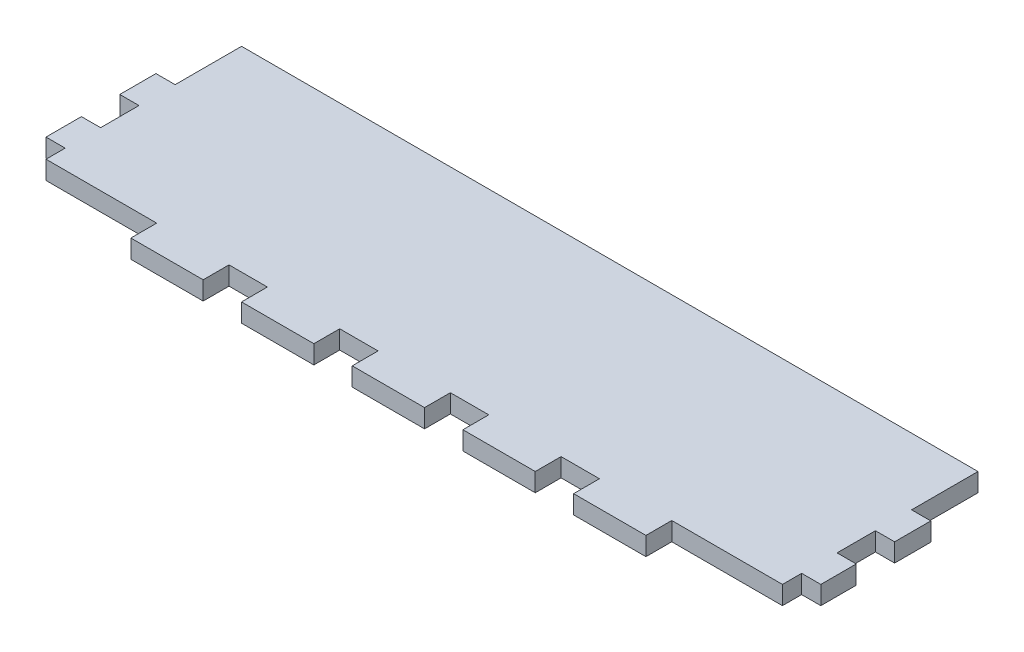
SolidWorks part; units mm, degrees
ref_plane "Front Plane" through (0, 0, 0) normal (0, 0, 1) x (1, 0, 0)
ref_plane "Top Plane" through (0, 0, 0) normal (0, 1, 0) x (1, 0, 0)
ref_plane "Right Plane" through (0, 0, 0) normal (1, 0, 0) x (0, 0, -1)
sketch "Sketch1" plane through (0, 0, 0) normal (0, 1, 0) x (1, 0, 0)
  line L2 (-133.35, -28.575) -> (-133.35, 28.575)
  line L3 (-133.35, 28.575) -> (133.35, 28.575)
  line L4 (133.35, -28.575) -> (133.35, 28.575)
  line L5 (-133.35, -28.575) -> (133.35, 28.575) construction
  line L6 (-133.35, 28.575) -> (133.35, -28.575) construction
  line L11 (-133.35, -28.575) -> (133.35, -28.575)
  point P0 (0, 0)
  dimension "D1" = 57.15
  dimension "D2" = 266.7
extrude "Boss-Extrude1" add sketch "Sketch1" along normal blind 6.35
sketch "Sketch3" plane through (0, 0, 0) normal (0, 1, 0) x (1, 0, 0)
  line L0 (-133.35, -28.575) -> (133.35, -28.575) construction
  line L1 (-88.646, -28.575) -> (-88.646, -37.465)
  line L2 (-88.646, -37.465) -> (-63.754, -37.465)
  line L3 (-63.754, -37.465) -> (-63.754, -28.575)
  line L4 (-63.754, -28.575) -> (-88.646, -28.575)
  line L5 (-50.546, -28.575) -> (-50.546, -37.465)
  line L6 (-50.546, -37.465) -> (-25.654, -37.465)
  line L7 (-25.654, -37.465) -> (-25.654, -28.575)
  line L8 (-25.654, -28.575) -> (-50.546, -28.575)
  line L9 (-12.446, -28.575) -> (-12.446, -37.465)
  line L10 (-12.446, -37.465) -> (12.446, -37.465)
  line L11 (12.446, -37.465) -> (12.446, -28.575)
  line L12 (12.446, -28.575) -> (-12.446, -28.575)
  line L13 (25.654, -28.575) -> (25.654, -37.465)
  line L14 (25.654, -37.465) -> (50.546, -37.465)
  line L15 (50.546, -37.465) -> (50.546, -28.575)
  line L16 (50.546, -28.575) -> (25.654, -28.575)
  line L17 (63.754, -28.575) -> (63.754, -37.465)
  line L18 (63.754, -37.465) -> (88.646, -37.465)
  line L19 (88.646, -37.465) -> (88.646, -28.575)
  line L20 (88.646, -28.575) -> (63.754, -28.575)
  point P0 (-76.2, -28.575)
  point P6 (-38.1, -28.575)
  point P14 (0, -28.575)
  point P19 (38.1, -28.575)
  point P24 (76.2, -28.575)
  dimension "D1" = 24.892
  dimension "D2" = 8.89
  dimension "D3" = 57.15
  dimension "D4" = 5
extrude "Boss-Extrude2" add sketch "Sketch3" along normal blind 6.35
sketch "Sketch4" plane through (0, 0, 0) normal (0, 1, 0) x (1, 0, 0)
  line L0 (133.35, 28.575) -> (-133.35, 28.575) construction
  line L6 (-139.954, 28.829) -> (-126.746, 28.829)
  line L7 (-139.954, 28.829) -> (-139.954, 15.621)
  line L8 (0, 0) -> (0, 63.6475) construction
  line L13 (133.35, -28.575) -> (133.35, 28.575) construction
  line L14 (126.746, 28.829) -> (139.954, 28.829)
  line L30 (126.746, 28.829) -> (126.746, 15.621)
  line L31 (126.746, 15.621) -> (139.954, 15.621)
  line L32 (139.954, 28.829) -> (139.954, 15.621)
  line L33 (126.746, 28.829) -> (139.954, 15.621) construction
  line L34 (126.746, 15.621) -> (139.954, 28.829) construction
  line L36 (-139.954, 15.621) -> (-126.746, 15.621)
  line L37 (-126.746, 28.829) -> (-126.746, 15.621)
  line L38 (-139.954, 28.829) -> (-126.746, 15.621) construction
  line L39 (-139.954, 15.621) -> (-126.746, 28.829) construction
  line L40 (-139.954, 3.429) -> (-126.746, 3.429)
  line L41 (-139.954, 3.429) -> (-139.954, -9.779)
  line L42 (-139.954, -9.779) -> (-126.746, -9.779)
  line L43 (-126.746, 3.429) -> (-126.746, -9.779)
  line L44 (-139.954, 3.429) -> (-126.746, -9.779) construction
  line L45 (-139.954, -9.779) -> (-126.746, 3.429) construction
  line L46 (-139.954, -21.971) -> (-126.746, -21.971)
  line L47 (-139.954, -21.971) -> (-139.954, -35.179)
  line L48 (-139.954, -35.179) -> (-126.746, -35.179)
  line L49 (-126.746, -21.971) -> (-126.746, -35.179)
  line L50 (-139.954, -21.971) -> (-126.746, -35.179) construction
  line L51 (-139.954, -35.179) -> (-126.746, -21.971) construction
  line L52 (126.746, 3.429) -> (139.954, 3.429)
  line L53 (126.746, 3.429) -> (126.746, -9.779)
  line L54 (126.746, -9.779) -> (139.954, -9.779)
  line L55 (139.954, 3.429) -> (139.954, -9.779)
  line L56 (126.746, 3.429) -> (139.954, -9.779) construction
  line L57 (126.746, -9.779) -> (139.954, 3.429) construction
  line L58 (126.746, -21.971) -> (139.954, -21.971)
  line L59 (126.746, -21.971) -> (126.746, -35.179)
  line L60 (126.746, -35.179) -> (139.954, -35.179)
  line L61 (139.954, -21.971) -> (139.954, -35.179)
  line L62 (126.746, -21.971) -> (139.954, -35.179) construction
  line L63 (126.746, -35.179) -> (139.954, -21.971) construction
  point P4 (-133.35, 22.225)
  point P10 (-133.35, -3.175)
  point P13 (133.35, 22.225)
  point P23 (-133.35, -28.575)
  point P29 (133.35, -3.175)
  point P34 (133.35, -28.575)
  dimension "D1" = 3
  dimension "D4" = 13.208
  dimension "D6" = 13.208
  dimension "D7" = 6.35
extrude "Cut-Extrude2" cut sketch "Sketch4" along normal through all
sketch "Sketch5" plane through (0, 6.35, 0) normal (0, 1, 0) x (1, 0, 0)
  line L0 (126.746, 28.575) -> (-126.746, 28.575) construction
  line L1 (-139.7688, 28.575) -> (155.6953, 28.575)
  line L2 (-139.7688, 28.575) -> (-139.7688, 15.875)
  line L3 (-139.7688, 15.875) -> (155.6953, 15.875)
  line L4 (155.6953, 28.575) -> (155.6953, 15.875)
  dimension "D1" = 12.7
extrude "Cut-Extrude3" cut sketch "Sketch5" against normal through all
sketch "Sketch6" plane through (0, 6.35, 0) normal (0, 1, 0) x (1, 0, 0)
  line L0 (133.35, 3.429) -> (133.35, 15.621) construction
  line L1 (-133.35, 3.429) -> (133.35, 3.429)
  line L2 (-133.35, 3.429) -> (-133.35, 15.875)
  line L3 (-133.35, 15.875) -> (133.35, 15.875)
  line L4 (133.35, 3.429) -> (133.35, 15.875)
  line L7 (-126.746, 15.875) -> (126.746, 15.875) construction
extrude "Boss-Extrude3" add sketch "Sketch6" against normal blind 6.35
sketch "Sketch7" plane through (0, 6.35, 0) normal (0, 1, 0) x (1, 0, 0)
  line L0 (-133.35, 15.875) -> (133.35, 15.875) construction
  line L1 (-126.746, 38.735) -> (126.746, 38.735)
  line L2 (-126.746, 38.735) -> (-126.746, 15.875)
  line L3 (-126.746, 15.875) -> (126.746, 15.875)
  line L4 (126.746, 38.735) -> (126.746, 15.875)
  line L5 (-126.746, -9.779) -> (-126.746, 3.429) construction
  line L6 (126.746, 3.429) -> (126.746, -9.779) construction
  line L7 (-88.646, -37.465) -> (-63.754, -37.465) construction
  dimension "D1" = 76.2
extrude "Boss-Extrude4" add sketch "Sketch7" against normal blind 6.35
